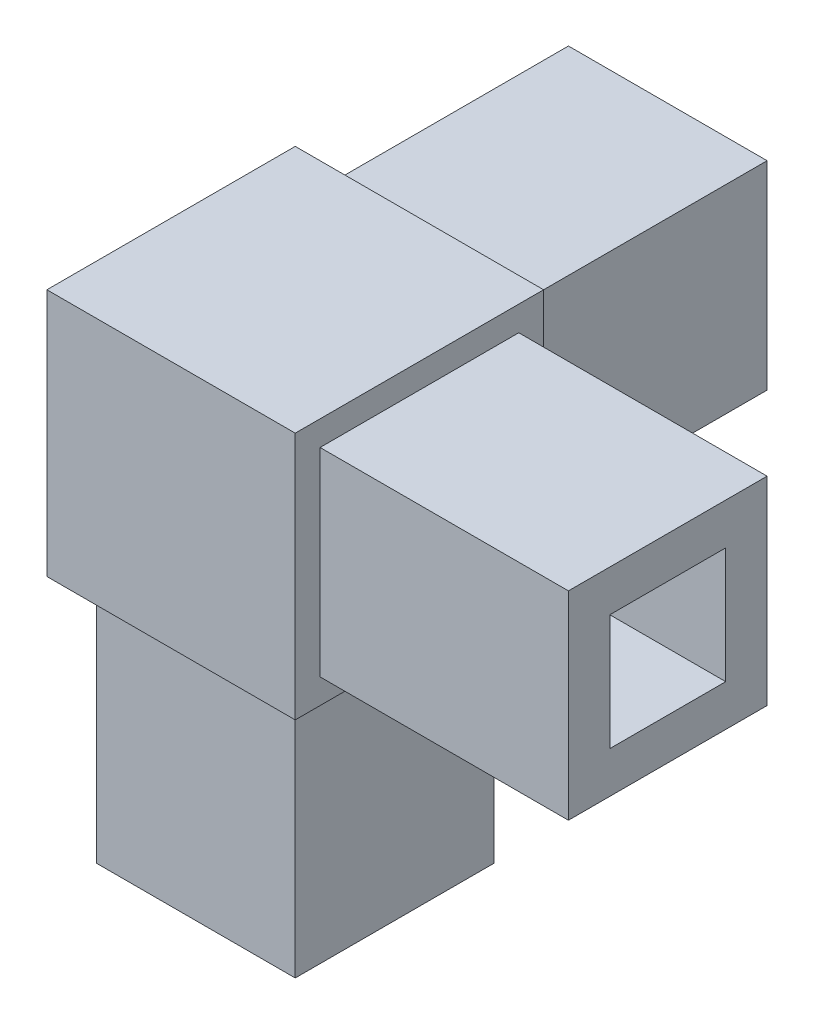
SolidWorks part; units mm, degrees
material "1060-H12"
ref_plane "Alzado" through (0, 0, 0) normal (0, 0, 1) x (1, 0, 0)
ref_plane "Planta" through (0, 0, 0) normal (0, 1, 0) x (1, 0, 0)
ref_plane "Vista lateral" through (0, 0, 0) normal (1, 0, 0) x (0, 0, -1)
sketch "Croquis1" plane through (0, 0, 0) normal (0, 1, 0) x (1, 0, 0)
  line L1 (15, -15) -> (-15, -15)
  line L2 (15, -15) -> (15, 15)
  line L3 (15, 15) -> (-15, 15)
  line L4 (-15, -15) -> (-15, 15)
  line L5 (15, -15) -> (-15, 15) construction
  line L6 (15, 15) -> (-15, -15) construction
  line L7 (15, -15) -> (45, -15)
  line L8 (15, -15) -> (15, 15)
  line L9 (15, 15) -> (45, 15)
  line L10 (45, -15) -> (45, 15)
  line L11 (-15, 15) -> (15, 15)
  line L12 (-15, 15) -> (-15, 45)
  line L13 (-15, 45) -> (15, 45)
  line L14 (15, 15) -> (15, 45)
  point P0 (0, 0)
  dimension "D1" = 30
  dimension "D2" = 30
  dimension "D3" = 30
  dimension "D4" = 30
extrude "Extruir1" add sketch "Croquis1" along normal blind 30 contours L3 L14 L13 L12 | L4 L1 L2 L3 | L7 L10 L9 L2
sketch "Croquis5" plane through (0, 0, 0) normal (0, -1, 0) x (1, 0, 0)
  line L1 (-15, 15) -> (15, 15)
  line L2 (-15, 15) -> (-15, -15)
  line L3 (-15, -15) -> (15, -15)
  line L4 (15, 15) -> (15, -15)
extrude "Extruir4" add sketch "Croquis5" along normal blind 30
sketch "Croquis2" plane through (45, 0, 0) normal (1, 0, 0) x (0, 0, -1)
  line L4 (-15, 0) -> (15, 0)
  line L5 (15, 0) -> (15, 30)
  line L6 (15, 30) -> (-15, 30)
  line L7 (-15, 30) -> (-15, 0)
  line L8 (-15, 0) -> (15, 0)
  line L9 (15, 0) -> (15, 30)
  line L10 (15, 30) -> (-15, 30)
  line L11 (-15, 30) -> (-15, 0)
  line L16 (-12, 3) -> (12, 3)
  line L17 (12, 3) -> (12, 27)
  line L18 (12, 27) -> (-12, 27)
  line L19 (-12, 27) -> (-12, 3)
  line L20 (-12, 3) -> (12, 3)
  line L21 (12, 3) -> (12, 27)
  line L22 (12, 27) -> (-12, 27)
  line L23 (-12, 27) -> (-12, 3)
  dimension "D1" = 0
  dimension "D2" = 3
extrude "Extruir2" cut sketch "Croquis2" against normal blind 30
sketch "Croquis3" plane through (0, 0, -45) normal (0, 0, -1) x (-1, 0, 0)
  line L0 (-12, 3) -> (12, 3)
  line L1 (12, 3) -> (12, 27)
  line L2 (12, 27) -> (-12, 27)
  line L3 (-12, 27) -> (-12, 3)
  line L4 (-15, 0) -> (15, 0)
  line L5 (15, 0) -> (15, 30)
  line L6 (15, 30) -> (-15, 30)
  line L7 (-15, 30) -> (-15, 0)
  line L8 (-15, 0) -> (15, 0)
  line L9 (15, 0) -> (15, 30)
  line L10 (15, 30) -> (-15, 30)
  line L11 (-15, 30) -> (-15, 0)
  dimension "D1" = 0
  dimension "D2" = 3
extrude "Extruir3" cut sketch "Croquis3" against normal blind 30
sketch "Croquis7" plane through (0, -30, 0) normal (0, -1, 0) x (1, 0, 0)
  line L0 (-12, 12) -> (-12, -12)
  line L1 (-12, -12) -> (12, -12)
  line L2 (12, -12) -> (12, 12)
  line L3 (12, 12) -> (-12, 12)
  line L4 (-15, 15) -> (-15, -15)
  line L5 (-15, -15) -> (15, -15)
  line L6 (15, -15) -> (15, 15)
  line L7 (15, 15) -> (-15, 15)
  line L8 (-15, 15) -> (-15, -15)
  line L9 (-15, -15) -> (15, -15)
  line L10 (15, -15) -> (15, 15)
  line L11 (15, 15) -> (-15, 15)
  dimension "D1" = 0
  dimension "D2" = 3
extrude "Extruir5" cut sketch "Croquis7" against normal blind 30
shell "Vaciado1" thickness 5
